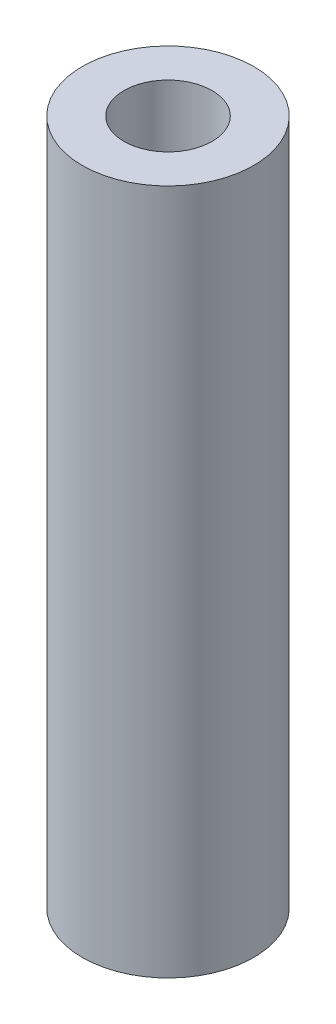
SolidWorks part; units mm, degrees
material "5052-O, Rod (SS)"
ref_plane "Front" through (0, 0, 0) normal (0, 0, 1) x (1, 0, 0)
ref_plane "Top" through (0, 0, 0) normal (0, 1, 0) x (1, 0, 0)
ref_plane "Right" through (0, 0, 0) normal (1, 0, 0) x (0, 0, -1)
sketch "Sketch1" plane through (0, 0, 0) normal (0, 1, 0) x (1, 0, 0)
  circle A0 centre (0, 0) radius 3.175
  dimension "D1" = 6.35
extrude "Boss-Extrude1" add sketch "Sketch1" along normal blind 25.4
sketch "Sketch2" plane through (0, 25.4, 0) normal (0, 1, 0) x (1, 0, 0)
  circle A0 centre (0, 0) radius 1.632
  dimension "D1" = 3.2639
extrude "Cut-Extrude1" cut sketch "Sketch2" against normal through all
